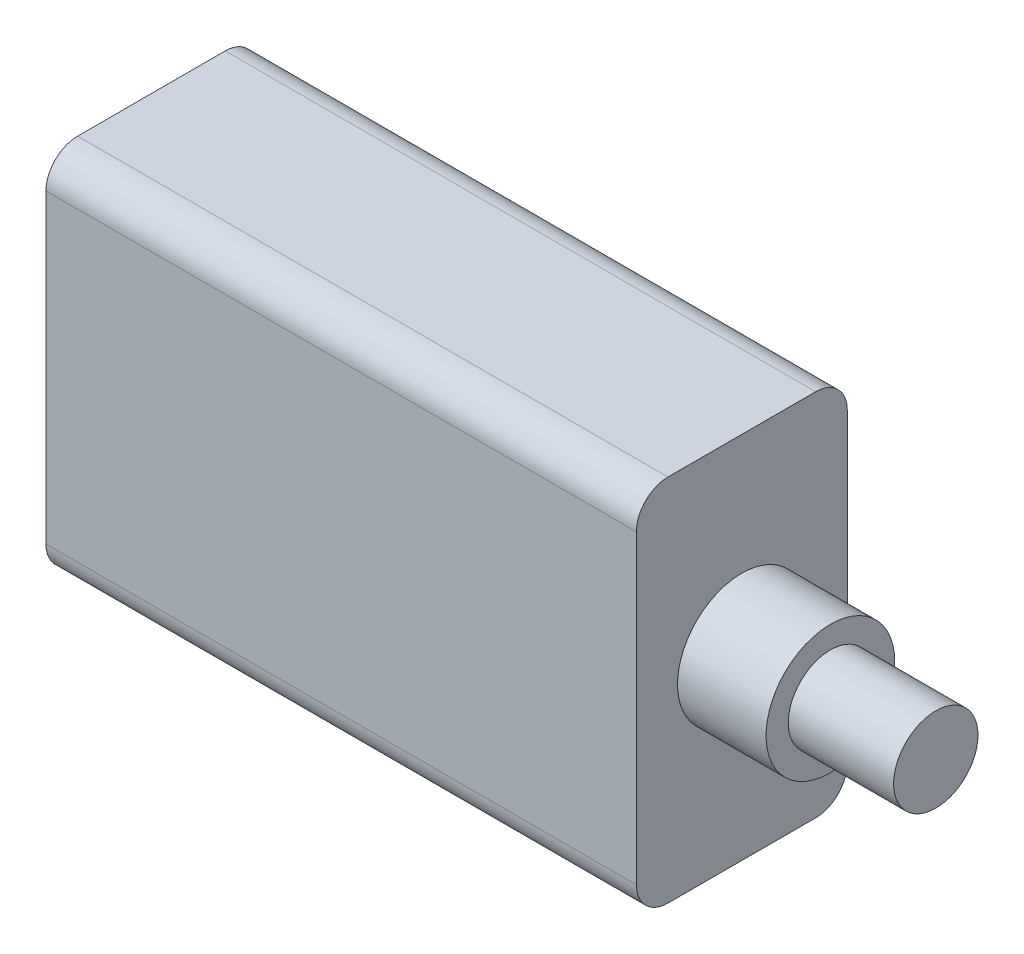
SolidWorks part; units mm, degrees
ref_plane "Front Plane" through (0, 0, 0) normal (0, 0, 1) x (1, 0, 0)
ref_plane "Top Plane" through (0, 0, 0) normal (0, 1, 0) x (1, 0, 0)
ref_plane "Right Plane" through (0, 0, 0) normal (1, 0, 0) x (0, 0, -1)
sketch "Sketch1" plane through (0, 0, 0) normal (0, 0, 1) x (1, 0, 0)
  line L1 (0, 0) -> (28, 0)
  line L2 (0, 0) -> (0, 17.5)
  line L3 (0, 17.5) -> (28, 17.5)
  line L4 (28, 0) -> (28, 17.5)
  dimension "D1" = 28
  dimension "D2" = 17.5
extrude "Boss-Extrude1" add sketch "Sketch1" along normal blind 10
sketch "Sketch3" plane through (0, 0, 0) normal (-1, 0, 0) x (0, 0, 1)
  line L0 (5, 17.5) -> (5, 0) construction
  line L1 (10, 17.5) -> (0, 17.5) construction
  line L2 (10, 0) -> (0, 0) construction
  line L3 (5, 0) -> (0, 8.75) construction
  line L4 (0, 17.5) -> (0, 0) construction
  line L5 (0, 8.75) -> (10, 8.75) construction
  line L6 (10, 17.5) -> (10, 0) construction
  line L8 (2.7, 14.75) -> (7.3, 14.75)
  line L9 (2.7, 14.75) -> (2.7, 2.75)
  line L10 (2.7, 2.75) -> (7.3, 2.75)
  line L11 (7.3, 14.75) -> (7.3, 2.75)
  line L12 (2.7, 14.75) -> (7.3, 2.75) construction
  line L13 (2.7, 2.75) -> (7.3, 14.75) construction
  point P12 (5, 8.75)
  dimension "D1" = 12
  dimension "D2" = 4.6
extrude "Cut-Extrude1" cut sketch "Sketch3" against normal blind 8.6
sketch "Sketch4" plane through (28, 0, 0) normal (1, 0, 0) x (0, 0, -1)
  line L0 (-10, 17.5) -> (0, 0) construction
  line L1 (-10, 0) -> (0, 17.5) construction
  circle A0 centre (-5, 8.75) radius 3.05
  dimension "D1" = 6.1
extrude "Boss-Extrude2" add sketch "Sketch4" along normal blind 4.2
sketch "Sketch5" plane through (32.2, 0, 0) normal (1, 0, 0) x (0, 0, -1)
  circle A0 centre (-5, 8.75) radius 2
  dimension "D1" = 4
extrude "Boss-Extrude3" add sketch "Sketch5" along normal blind 5
fillet "Fillet1" radius 1.5 4 edges at (14, 17.5, 0) (14, 0, 0) (14, 0, 10) (14, 17.5, 10)
